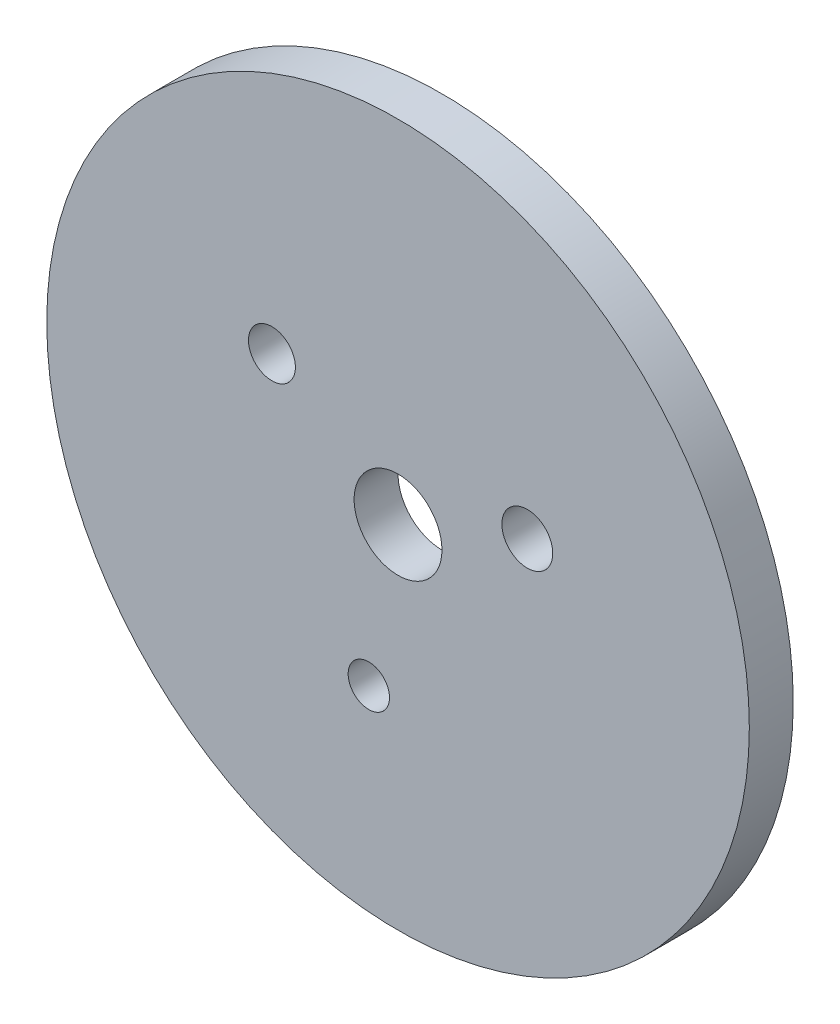
SolidWorks part; units mm, degrees
ref_plane "Front Plane" through (0, 0, 0) normal (0, 0, 1) x (1, 0, 0)
ref_plane "Top Plane" through (0, 0, 0) normal (0, 1, 0) x (1, 0, 0)
ref_plane "Right Plane" through (0, 0, 0) normal (1, 0, 0) x (0, 0, -1)
sketch "Sketch1" plane through (0, 0, 0) normal (0, 0, 1) x (1, 0, 0)
  circle A0 centre (0, 0) radius 25.4
  circle A1 centre (0, 0) radius 3.175
  dimension "D1" = 50.8
  dimension "D2" = 6.35
extrude "Boss-Extrude1" add sketch "Sketch1" along normal blind 3.175
sketch "AttachmentHoles" plane through (0, 0, 0) normal (0, 0, 1) x (1, 0, 0)
  circle A0 centre (-9.1189, 6.1459) radius 1.6976
  circle A1 centre (9.3472, 3.792) radius 1.8394
  circle A2 centre (-2.1134, -11.1403) radius 1.4941
extrude "Cut-Extrude1" cut sketch "AttachmentHoles" along normal through all
